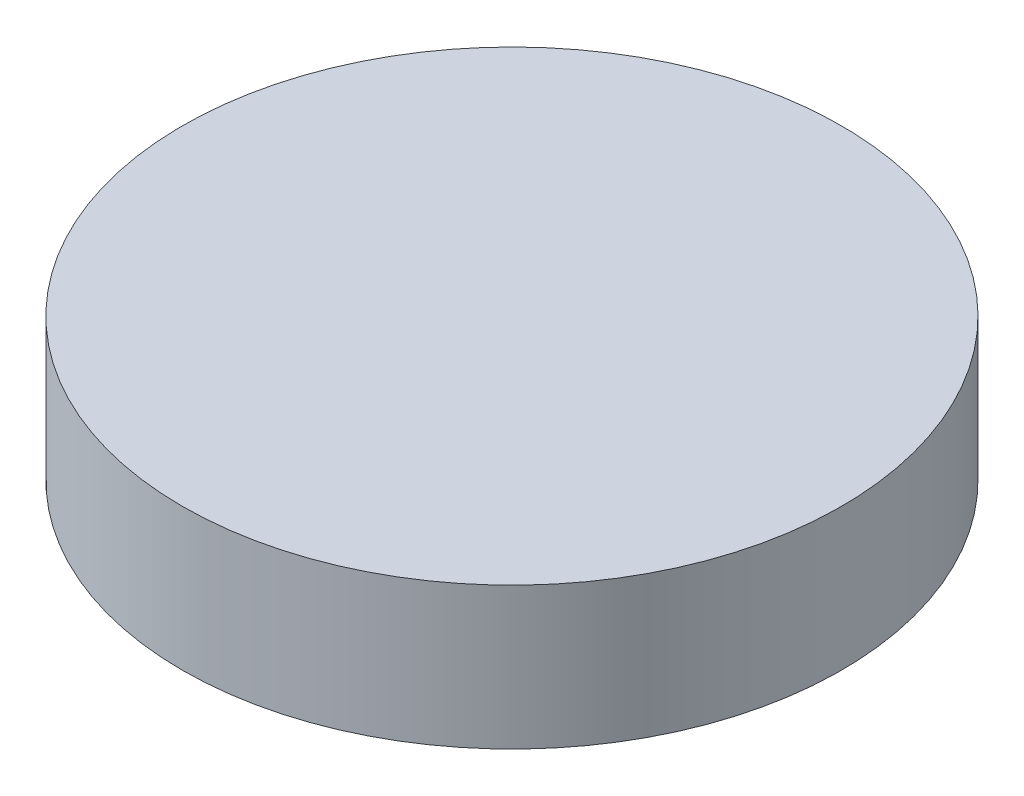
SolidWorks part; units mm, degrees
ref_plane "Front Plane" through (0, 0, 0) normal (0, 0, 1) x (1, 0, 0)
ref_plane "Top Plane" through (0, 0, 0) normal (0, 1, 0) x (1, 0, 0)
ref_plane "Right Plane" through (0, 0, 0) normal (1, 0, 0) x (0, 0, -1)
sketch "Sketch1" plane through (0, 0, 0) normal (0, 1, 0) x (1, 0, 0)
  circle A0 centre (0, 0) radius 13.93
extrude "Boss-Extrude1" add sketch "Sketch1" along normal blind 6
